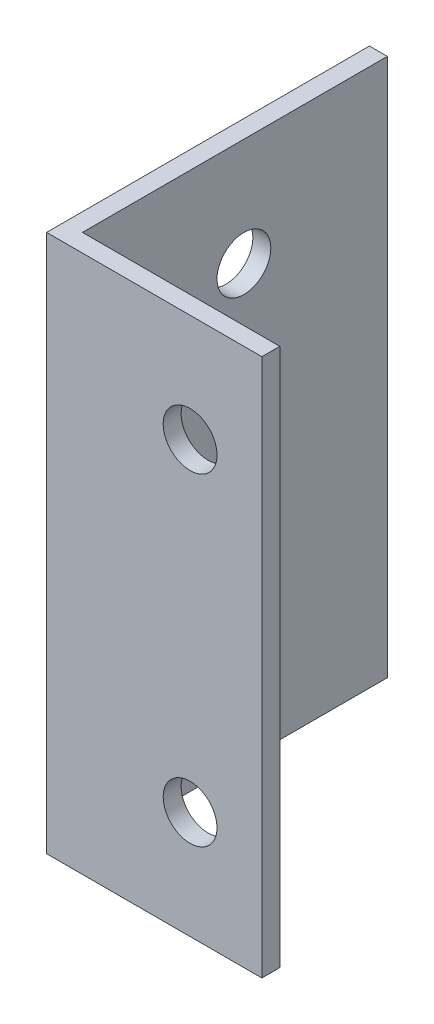
SolidWorks part; units mm, degrees
material "6061 合金"
ref_plane "前视基准面" through (0, 0, 0) normal (0, 0, 1) x (1, 0, 0)
ref_plane "上视基准面" through (0, 0, 0) normal (0, 1, 0) x (1, 0, 0)
ref_plane "右视基准面" through (0, 0, 0) normal (1, 0, 0) x (0, 0, -1)
sketch "草图4" plane through (0, 0, 0) normal (0, 1, 0) x (1, 0, 0)
  line L0 (0, 0) -> (0, 18)
  line L1 (0, 18) -> (1, 18)
  line L2 (1, 18) -> (1, 1)
  line L3 (1, 1) -> (12, 1)
  line L4 (12, 1) -> (12, 0)
  line L5 (12, 0) -> (0, 0)
  dimension "D1" = 12
  dimension "D2" = 18
  dimension "D3" = 1
extrude "凸台-拉伸2" add sketch "草图4" along normal blind 30
sketch "草图5" plane through (0, 0, -1) normal (0, 0, -1) x (-1, 0, 0)
  line L0 (-8, 30) -> (-8, 0) construction
  line L1 (-12, 30) -> (-1, 30) construction
  line L2 (-12, 0) -> (-1, 0) construction
  line L3 (-12, 30) -> (-12, 0) construction
  line L4 (-12, 15) -> (-1, 15) construction
  line L5 (-1, 30) -> (-1, 0) construction
  circle A0 centre (-8, 6) radius 1.5
  circle A1 centre (-8, 24) radius 1.5
  dimension "D2" = 3
  dimension "D1" = 4
  dimension "D3" = 9
extrude "切除-拉伸3" cut sketch "草图5" against normal through all
sketch "草图6" plane through (1, 0, 0) normal (1, 0, 0) x (0, 0, -1)
  line L0 (10, 30) -> (10, 0) construction
  line L1 (1, 30) -> (18, 30) construction
  line L2 (1, 0) -> (18, 0) construction
  line L3 (18, 30) -> (18, 0) construction
  line L4 (18, 15) -> (1, 15) construction
  line L5 (1, 30) -> (1, 0) construction
  circle A0 centre (10, 24) radius 1.5
  circle A1 centre (10, 6) radius 1.5
  dimension "D2" = 9
  dimension "D3" = 3
  dimension "D1" = 8
extrude "切除-拉伸4" cut sketch "草图6" against normal through all
